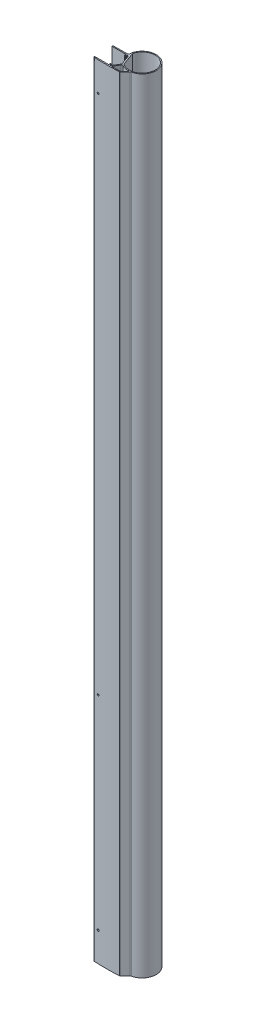
SolidWorks part; units mm, degrees
material "5052-H32"
ref_plane "Front Plane" through (0, 0, 0) normal (0, 0, 1) x (1, 0, 0)
ref_plane "Top Plane" through (0, 0, 0) normal (0, 1, 0) x (1, 0, 0)
ref_plane "Right Plane" through (0, 0, 0) normal (1, 0, 0) x (0, 0, -1)
sketch "Sketch1" plane through (0, 0, 0) normal (0, 1, 0) x (1, 0, 0)
  line L0 (-32.4987, 7.4225) -> (-20.1244, -26.5757)
  line L1 (-7.8548, -47.0262) -> (1.4723, -37.6992)
  line L2 (-21.8713, -32.3782) -> (-30.2459, -46.6278)
  line L3 (-37.9472, 0.5068) -> (-73.0001, 0)
  line L4 (-75.0001, -2) -> (-75.0001, -2.5)
  line L5 (-75.0001, -2.5) -> (-39.9975, -2.5)
  line L6 (-38.9975, -3.5) -> (-38.9975, -6.3)
  line L7 (-38.7975, -6.5) -> (-36.6975, -6.5)
  line L8 (-36.4975, -6.3) -> (-36.4975, -3.5)
  line L9 (-35.4975, -2.5) -> (-35.4126, -2.5)
  line L10 (-35.4126, -2.5) -> (-34.3623, -2.5)
  line L11 (-32.0131, -4.1449) -> (-29.9393, -9.8428)
  line L12 (-29.8358, -9.9557) -> (-28.9281, -10.3784)
  line L13 (-28.8313, -10.6442) -> (-29.2547, -11.5525)
  line L14 (-29.2613, -11.7054) -> (-25.5092, -22.0142)
  line L15 (-25.4057, -22.1271) -> (-24.5014, -22.5483)
  line L16 (-24.4046, -22.8141) -> (-24.8264, -23.7191)
  line L17 (-24.833, -23.872) -> (-23.38, -27.8642)
  line L18 (-23.6162, -30.4164) -> (-32.9846, -46.2717)
  line L19 (-35.137, -47.5) -> (-35.4223, -47.5)
  line L20 (-35.4223, -47.5) -> (-35.4975, -47.5)
  line L21 (-36.4975, -46.5) -> (-36.4975, -42.7)
  line L22 (-36.6975, -42.5) -> (-38.7975, -42.5)
  line L23 (-38.9975, -42.7) -> (-38.9975, -46.5)
  line L24 (-39.9975, -47.5) -> (-75.0001, -47.5)
  line L25 (-75.0001, -47.5) -> (-75.0001, -47.992)
  line L26 (-6.9735, -48.9733) -> (5.5562, -36.4437)
  line L27 (-0.0001, 0) -> (-0.0001, -80.2752) construction
  arc A0 (-32.53, 8.0035) -> (-32.4987, 7.4225) centre (-31.559, 7.7645) ccw
  arc A1 (-20.1244, -26.5757) -> (-19.775, -27.0408) centre (-19.1847, -26.2336) ccw
  arc A2 (-19.775, -27.0408) -> (-32.53, 8.0035) centre (-0.0001, 0) ccw
  arc A3 (7.9829, -35.1037) -> (-34.9784, 8.5159) centre (-0.0001, 0) ccw
  arc A4 (-34.9784, 8.5159) -> (-35.0532, 4.1166) centre (-25.2622, 6.1504) ccw
  arc A5 (-37.9472, 0.5068) -> (-35.0532, 4.1166) centre (-37.9905, 3.5065) ccw
  arc A6 (-73.0001, 0) -> (-75.0001, -2) centre (-73.0001, -2) ccw
  arc A7 (-38.9975, -3.5) -> (-39.9975, -2.5) centre (-39.9975, -3.5) ccw
  arc A8 (-38.9975, -6.3) -> (-38.7975, -6.5) centre (-38.7975, -6.3) ccw
  arc A9 (-36.6975, -6.5) -> (-36.4975, -6.3) centre (-36.6975, -6.3) ccw
  arc A10 (-35.4975, -2.5) -> (-36.4975, -3.5) centre (-35.4975, -3.5) ccw
  arc A11 (-32.0131, -4.1449) -> (-34.3623, -2.5) centre (-34.3623, -5) ccw
  arc A12 (-29.9393, -9.8428) -> (-29.8358, -9.9557) centre (-29.7513, -9.7744) ccw
  arc A13 (-28.8313, -10.6442) -> (-28.9281, -10.3784) centre (-29.0126, -10.5597) ccw
  arc A14 (-29.2547, -11.5525) -> (-29.2613, -11.7054) centre (-29.0734, -11.637) ccw
  arc A15 (-25.5092, -22.0142) -> (-25.4057, -22.1271) centre (-25.3213, -21.9458) ccw
  arc A16 (-24.4046, -22.8141) -> (-24.5014, -22.5483) centre (-24.5858, -22.7296) ccw
  arc A17 (-24.8264, -23.7191) -> (-24.833, -23.872) centre (-24.6451, -23.8036) ccw
  arc A18 (-23.6162, -30.4164) -> (-23.38, -27.8642) centre (-26.1991, -28.8903) ccw
  arc A19 (-35.137, -47.5) -> (-32.9846, -46.2717) centre (-35.137, -45) ccw
  arc A20 (-36.4975, -46.5) -> (-35.4975, -47.5) centre (-35.4975, -46.5) ccw
  arc A21 (-36.4975, -42.7) -> (-36.6975, -42.5) centre (-36.6975, -42.7) ccw
  arc A22 (-38.7975, -42.5) -> (-38.9975, -42.7) centre (-38.7975, -42.7) ccw
  arc A23 (-39.9975, -47.5) -> (-38.9975, -46.5) centre (-39.9975, -46.5) ccw
  arc A24 (-75.0001, -47.992) -> (-73.1788, -49.984) centre (-73.0001, -47.992) ccw
  arc A25 (-73.1788, -49.984) -> (-8.8133, -49.8388) centre (-42.3502, 550.1611) ccw
  arc A26 (-8.8133, -49.8388) -> (-6.9735, -48.9733) centre (-9.0948, -46.852) ccw
  arc A27 (7.9829, -35.1037) -> (5.5562, -36.4437) centre (9.0917, -39.9792) ccw
  arc A28 (-30.2459, -46.6278) -> (-29.3621, -48.1343) centre (-29.3838, -47.1345) ccw
  arc A29 (-29.3621, -48.1343) -> (-8.5053, -47.3175) centre (-42.3484, 550.1613) ccw
  arc A30 (-8.5053, -47.3175) -> (-7.8548, -47.0262) centre (-8.5619, -46.3191) ccw
  arc A31 (1.4723, -37.6992) -> (0.7445, -35.9923) centre (0.7652, -36.9921) ccw
  arc A32 (-17.8015, -31.2907) -> (0.7445, -35.9923) centre (0, 0) ccw
  arc A33 (-17.8015, -31.2907) -> (-21.8713, -32.3782) centre (-19.2849, -33.8982) ccw
  point P95 (-37.7475, -42.5)
  dimension "D1" = 36
  dimension "D2" = 33.5
  dimension "D7" = 3
  dimension "D8" = 1
  dimension "D3" = 45
  dimension "D4" = 5
  dimension "D5" = 2.5
  dimension "D6" = 3.5
extrude "Boss-Extrude1" add sketch "Sketch1" along normal mid plane 2017
sketch "Sketch4" plane through (0, -1008.5, 0) normal (0, -1, 0) x (1, 0, 0)
  line L0 (4.1855, 43.8002) -> (-51.0745, 32.7637) construction
  line L1 (1.4875, 48.3601) -> (3.446, 38.5538) construction
  line L2 (-6.9735, 48.9733) -> (5.5562, 36.4437) construction
  line L3 (1.4875, 48.3601) -> (-46.6615, 38.7438) construction
  line L4 (-46.6615, 38.7438) -> (-44.703, 28.9374) construction
  line L5 (-44.703, 28.9374) -> (3.446, 38.5538) construction
  point P4 (2.4668, 43.457)
  dimension "D1" = 10
ref_plane "Plane1" through (10.7185, 0, 2.1407) normal (0.9806, 0, 0.1959) x (0.1959, 0, -0.9806)
sketch "Sketch5" plane through (10.7185, 0, 2.1407) normal (0.9806, 0, 0.1959) x (0.1959, 0, -0.9806)
  line L0 (-49.3906, -1008.5) -> (-34.6497, -1008.5) construction
  circle A0 centre (-42.0202, -948.5) radius 2
  point P5 (-42.0202, -1008.5)
  dimension "D1" = 4
  dimension "D2" = 60
extrude "Cut-Extrude2" [suppressed] cut sketch "Sketch5" against normal through all
sketch "Sketch6" [suppressed] plane through (10.7186, 0, 2.1408) normal (0.9806, 0, 0.1959) x (0.1959, 0, -0.9806)
  circle A0 centre (-42.0201, -990) radius 5
  dimension "D1" = 10
extrude "Cut-Extrude3" [suppressed] cut sketch "Sketch6" against normal up to next
sketch "Sketch7" plane through (0, 1008.5, 0) normal (0, -1, 0) x (1, 0, 0)
  line L0 (-43.7971, -13.1877) -> (-9.2546, 56.2657)
  line L1 (-40.3078, -9.9347) -> (3.8728, 70.9767) construction
  arc A2 (-43.7971, -13.1877) -> (-9.2546, 56.2657) centre (61.7074, -22.3436) ccw
  arc A3 (-6.9735, 48.9733) -> (-8.8133, 49.8388) centre (-9.0948, 46.852) ccw construction
  point P3 (-35.4975, 3.5)
  point P15 (-7.8178, 49.5667)
extrude "Cut-Extrude4" [suppressed] cut sketch "Sketch7" along normal blind 10
ref_plane "Plane2" through (0, 0, -36) normal (0, 0, -1) x (-1, 0, 0)
sketch "Sketch9" plane through (0, 0, -36) normal (0, 0, -1) x (-1, 0, 0)
  line L0 (37.9472, -1008.5) -> (73.0001, -1008.5) construction
  line L1 (271.2396, 1247.703) -> (-158.0526, 1247.703)
  line L2 (271.2396, 1247.703) -> (271.2396, 1050)
  line L3 (271.2396, 1050) -> (-158.0526, 1050)
  line L4 (-158.0526, 1247.703) -> (-158.0526, 1050)
  point P6 (55.4737, -1008.5)
  dimension "D1" = 2058.5
extrude "Cut-Extrude6" [suppressed] cut sketch "Sketch9" against normal through all
ref_plane "Plane4" through (0, -1008.5, 0) normal (0, -1, 0) x (-1, 0, 0)
sketch "Sketch14" plane through (0, -1008.5, 0) normal (0, -1, 0) x (-1, 0, 0)
  line L0 (0, 0) -> (34.0543, -12.3948) construction
sketch "Sketch10" [suppressed] plane through (-29.6004, 0, 10.7737) normal (-0.9397, 0, 0.342) x (0.342, 0, 0.9397)
  line L0 (11.9619, 1201) -> (0.9915, 1201) construction
  line L1 (0, 1201) -> (0, 1186) construction
  line L3 (0.1414, 1201) -> (-0.1414, 1201) construction
  circle A0 centre (0, 1186) radius 2.5
  circle A1 centre (0, 1136) radius 2.5
  point P17 (0, 1201)
  dimension "D1" = 5
  dimension "D2" = 65
  dimension "D3" = 15
extrude "Cut-Extrude7" [suppressed] cut sketch "Sketch10" against normal up to next
sketch "Sketch11" plane through (-29.6004, 0, 10.7737) normal (-0.9397, 0, 0.342) x (0.342, 0, 0.9397)
  line L0 (-7.0542, -1008.5) -> (-0.9906, -1008.5) construction
  line L1 (-107.4227, 0) -> (162.177, 0) construction
  line L4 (0, -1211.666) -> (0, 1230.1361) construction
  circle A0 centre (0, -963.5) radius 4.5
  circle A1 centre (0, -864.5) radius 4.5
  circle A2 centre (0, 963.5) radius 4.5
  circle A3 centre (0, 864.5) radius 4.5
  point P14 (-4.0224, -1008.5)
  dimension "D1" = 9
  dimension "D2" = 99
  dimension "D4" = 45
extrude "Cut-Extrude8" cut sketch "Sketch11" against normal up to next
sketch "Sketch12" plane through (0.0104, 0, 2.5) normal (0, 0, -1) x (-1, 0, 0)
  line L0 (37.9576, -1008.5) -> (73.0106, -1008.5) construction
  line L1 (37.9576, 1008.5) -> (73.0106, 1008.5) construction
  circle A0 centre (63.0106, -933.5) radius 2.5
  circle A1 centre (63.0106, -408.5) radius 2.5
  circle A2 centre (63.0106, 933.5) radius 2.5
  dimension "D2" = 600
  dimension "D3" = 5
  dimension "D4" = 12
  dimension "D1" = 75
  dimension "D5" = 75
extrude "Cut-Extrude9" cut sketch "Sketch12" against normal through all and the other way through all
sketch "Sketch13" plane through (0, -1008.5, 0) normal (0, -1, 0) x (-1, 0, 0)
  line L0 (26.3115, -9.5766) -> (0, 0) construction
  line L1 (32.4987, 7.4225) -> (20.1244, -26.5757) construction
  line L2 (0, 0) -> (-12.3127, -33.8289) construction
  line L3 (1.475, -38.8472) -> (-26.1005, -28.8106) construction
  arc A0 (34.9784, 8.5159) -> (-7.9829, -35.1037) centre (0.0001, 0) ccw construction
  point P9 (-12.3127, -33.8289)
ref_plane "Plane3" through (12.3127, 0, 33.8289) normal (0.342, 0, 0.9397) x (0.9397, 0, -0.342)
